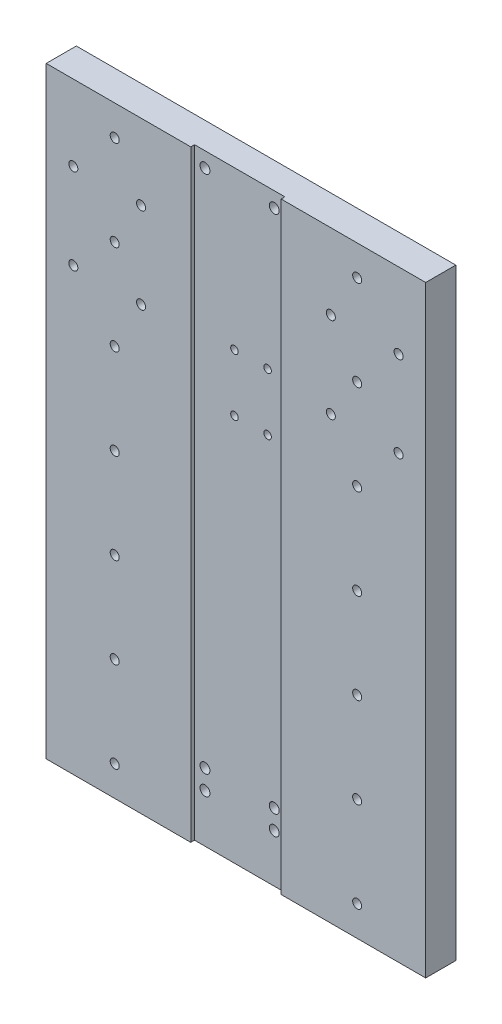
SolidWorks part; units mm, degrees
ref_plane "Piano frontale" through (0, 0, 0) normal (0, 0, 1) x (1, 0, 0)
ref_plane "Piano superiore" through (0, 0, 0) normal (0, 1, 0) x (1, 0, 0)
ref_plane "Piano destro" through (0, 0, 0) normal (1, 0, 0) x (0, 0, -1)
sketch "Schizzo1" plane through (0, 0, 0) normal (0, 0, 1) x (1, 0, 0)
  line L1 (126, -200) -> (-126, -200)
  line L2 (126, -200) -> (126, 200)
  line L3 (126, 200) -> (-126, 200)
  line L4 (-126, -200) -> (-126, 200)
  line L5 (126, -200) -> (-126, 200) construction
  line L6 (126, 200) -> (-126, -200) construction
  point P0 (0, 0)
  dimension "D1" = 252
  dimension "D2" = 400
extrude "Estrusione-Estrusione1" add sketch "Schizzo1" along normal blind 20
sketch "Schizzo2" plane through (0, 0, 20) normal (0, 0, 1) x (1, 0, 0)
  line L0 (1265.2426, 21.4119) -> (-695.7574, 21.4119) construction
  line L1 (1265.2426, 13.5541) -> (-695.7574, 13.5541) construction
  line L2 (1265.2426, 53.5541) -> (-695.7574, 53.5541) construction
  line L3 (1265.2426, 61.4119) -> (-695.7574, 61.4119) construction
  line L4 (-126, 200) -> (-126, -200)
  line L5 (-126, -200) -> (126, -200)
  line L6 (126, -200) -> (126, 200)
  line L7 (126, 200) -> (-126, 200)
  line L8 (-126, 200) -> (-126, -200) construction
  line L9 (-126, -200) -> (126, -200) construction
  line L10 (126, -200) -> (126, 200) construction
  line L11 (126, 200) -> (-126, 200) construction
  line L12 (1265.2426, 21.4119) -> (-695.7574, 21.4119) construction
  line L13 (1265.2426, 13.5541) -> (-695.7574, 13.5541) construction
  line L14 (1265.2426, 53.5541) -> (-695.7574, 53.5541) construction
  line L15 (1265.2426, 61.4119) -> (-695.7574, 61.4119) construction
  line L16 (126, -45.017) -> (-126, -45.017) construction
  line L17 (126, -25.017) -> (-126, -25.017) construction
  line L18 (126, -45.017) -> (-126, -45.017) construction
  line L19 (126, -25.017) -> (-126, -25.017) construction
  line L20 (-126, -45.017) -> (-126, -25.017) construction
  line L21 (126, -35.017) -> (-126, -35.017) construction
  line L22 (-126, -45.017) -> (126, -45.017) construction
  line L23 (-126, -45.017) -> (-126, -25.017) construction
  line L24 (-126, -25.017) -> (126, -25.017) construction
  line L25 (126, -45.017) -> (126, -25.017) construction
  circle A0 centre (110, 17.483) radius 3.9289
  circle A1 centre (110, 57.483) radius 3.9289
  circle A2 centre (-110, 17.483) radius 3.9289
  circle A3 centre (-110, 57.483) radius 3.9289
  circle A4 centre (110, -35.017) radius 3.5
  circle A5 centre (-110, -35.017) radius 3.5
  circle A6 centre (55, -35.017) radius 3.5
  circle A8 centre (-55, -35.017) radius 3.5
  circle A9 centre (20, -35.017) radius 3.5
  circle A10 centre (-20, -35.017) radius 3.5
  circle A11 centre (165, -35.017) radius 3.5 [skipped]
  dimension "D2" = 16
  dimension "D3" = 7.8579
  dimension "D4" = 16
  dimension "D5" = 7.8579
  dimension "D6" = 7
  dimension "D7" = 7
  dimension "D8" = 2
  dimension "D1" = 0
  dimension "D9" = 2
  dimension "D10" = 2
  dimension "D11" = 2
sketch "Schizzo3" plane through (0, 200, 0) normal (0, 1, 0) x (1, 0, 0)
  line L0 (126, -20) -> (-126, -20) construction
  line L1 (30, -17.5) -> (-30, -17.5)
  line L2 (30, -17.5) -> (30, -29.5854)
  line L3 (30, -29.5854) -> (-30, -29.5854)
  line L4 (-30, -17.5) -> (-30, -29.5854)
  dimension "D1" = 2.5
extrude "Taglio-Estrusione1" cut sketch "Schizzo3" against normal through all
sketch "Schizzo4" plane through (0, 0, 17.5) normal (0, 0, 1) x (1, 0, 0)
  circle A2 centre (22.9236, 190) radius 3.3
  circle A3 centre (-23.0764, 190) radius 3.3
  circle A6 centre (22.9236, -155) radius 3.3
  circle A7 centre (-23.0764, -155) radius 3.3
  circle A10 centre (22.9236, -168) radius 3.3
  circle A11 centre (-23.0764, -168) radius 3.3
extrude "Taglio-Estrusione2" cut sketch "Schizzo4" against normal through all
sketch "Schizzo5" plane through (0, 0, 20) normal (0, 0, 1) x (1, 0, 0)
  circle A5 centre (80.5006, -120) radius 3
  circle A6 centre (80.5006, -180) radius 3
  circle A7 centre (80.5006, 180) radius 3
  circle A8 centre (80.5006, 120) radius 3
  circle A9 centre (80.5006, 60) radius 3
  circle A12 centre (80.5006, 0) radius 3
  circle A13 centre (80.5006, -60) radius 3
extrude "Taglio-Estrusione3" cut sketch "Schizzo5" against normal through all
mirror "Specchia1" about plane through (0, 0, 0) normal (1, 0, 0) of "Taglio-Estrusione3"
sketch "Schizzo6" plane through (0, 0, 20) normal (0, 0, 1) x (1, 0, 0)
  circle A4 centre (108, 92.8083) radius 3
  circle A5 centre (63, 92.8083) radius 3
  circle A6 centre (108, 149.8083) radius 3
  circle A7 centre (63, 149.8083) radius 3
  circle A12 centre (-3.5, 95.3083) radius 2.5
  circle A13 centre (18.5, 95.3083) radius 2.5
  circle A14 centre (-3.5, 57.3083) radius 2.5
  circle A15 centre (18.5, 57.3083) radius 2.5
  circle A18 centre (-63, 92.8083) radius 3
  circle A19 centre (-108, 92.8083) radius 3
  circle A22 centre (-63, 149.8083) radius 3
  circle A23 centre (-108, 149.8083) radius 3
extrude "Taglio-Estrusione4" cut sketch "Schizzo6" against normal through all
